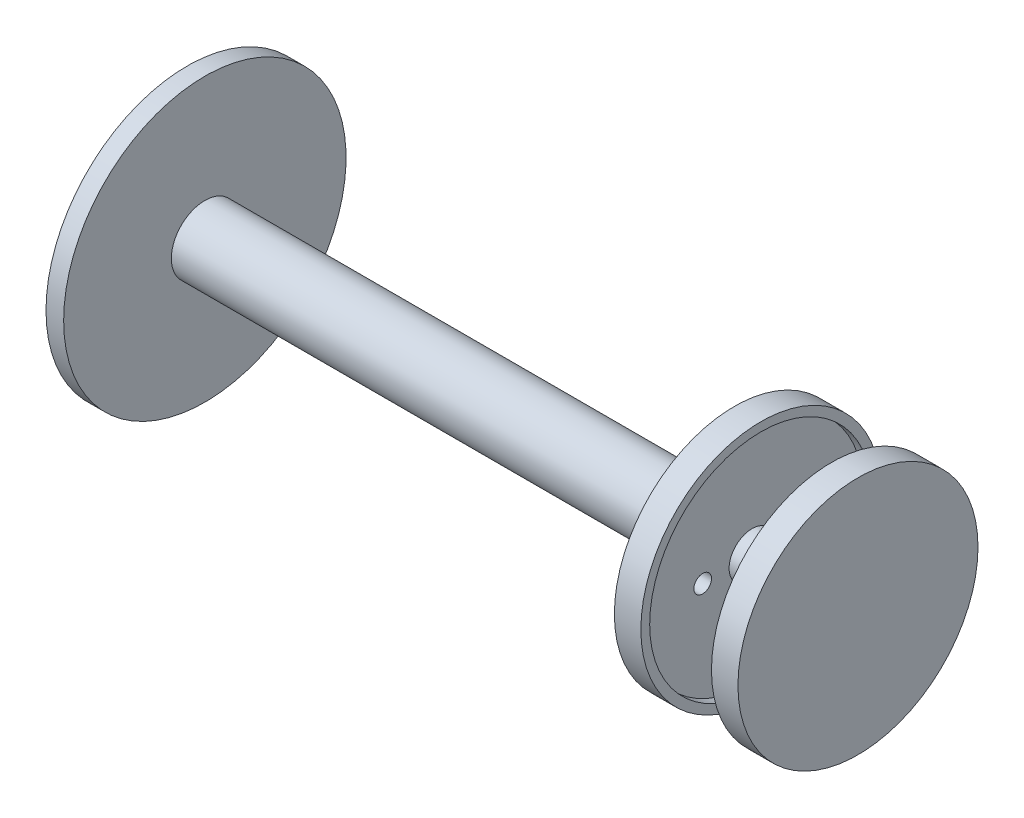
SolidWorks part; units mm, degrees
ref_plane "Front" through (0, 0, 0) normal (0, 0, 1) x (1, 0, 0)
ref_plane "Top" through (0, 0, 0) normal (0, 1, 0) x (1, 0, 0)
ref_plane "Right" through (0, 0, 0) normal (1, 0, 0) x (0, 0, -1)
sketch "Sketch1" plane through (0, 0, 0) normal (0, 0, 1) x (1, 0, 0)
  line L0 (-35.7804, 0) -> (34.2196, 0)
  line L1 (-35.7804, 0) -> (-35.7804, 68)
  line L2 (-35.7804, 68) -> (-20.7804, 68)
  line L3 (-20.7804, 68) -> (-20.7804, 63)
  line L4 (-20.7804, 63) -> (-25.7804, 63)
  line L5 (-25.7804, 63) -> (-25.7804, 13)
  line L6 (-25.7804, 13) -> (24.2196, 13)
  line L7 (24.2196, 13) -> (24.2196, 63)
  line L8 (24.2196, 63) -> (19.2196, 63)
  line L9 (19.2196, 63) -> (19.2196, 68)
  line L10 (19.2196, 68) -> (34.2196, 68)
  line L11 (34.2196, 68) -> (34.2196, 0)
  line L12 (-140.0826, 0) -> (107.6958, 0) construction
  dimension "D1" = 68
  dimension "D2" = 50
  dimension "D3" = 5
  dimension "D4" = 68
  dimension "D5" = 15
revolve "Revolve1" add sketch "Sketch1" angle 360 about L12
sketch "Sketch2" plane through (-35.7804, 0, 0) normal (-1, 0, 0) x (0, 0, 1)
  circle A0 centre (0, 0) radius 19
extrude "Boss-Extrude1" add sketch "Sketch2" along normal blind 300
sketch "Sketch3" plane through (-35.7804, 0, 0) normal (-1, 0, 0) x (0, 0, 1)
  circle A0 centre (27.9616, 0) radius 5
extrude "Cut-Extrude1" cut sketch "Sketch3" against normal blind 10
sketch "Sketch4" plane through (-335.7804, 0, 0) normal (-1, 0, 0) x (0, 0, 1)
  circle A0 centre (0, 0) radius 80
extrude "Boss-Extrude2" add sketch "Sketch4" along normal blind 10
